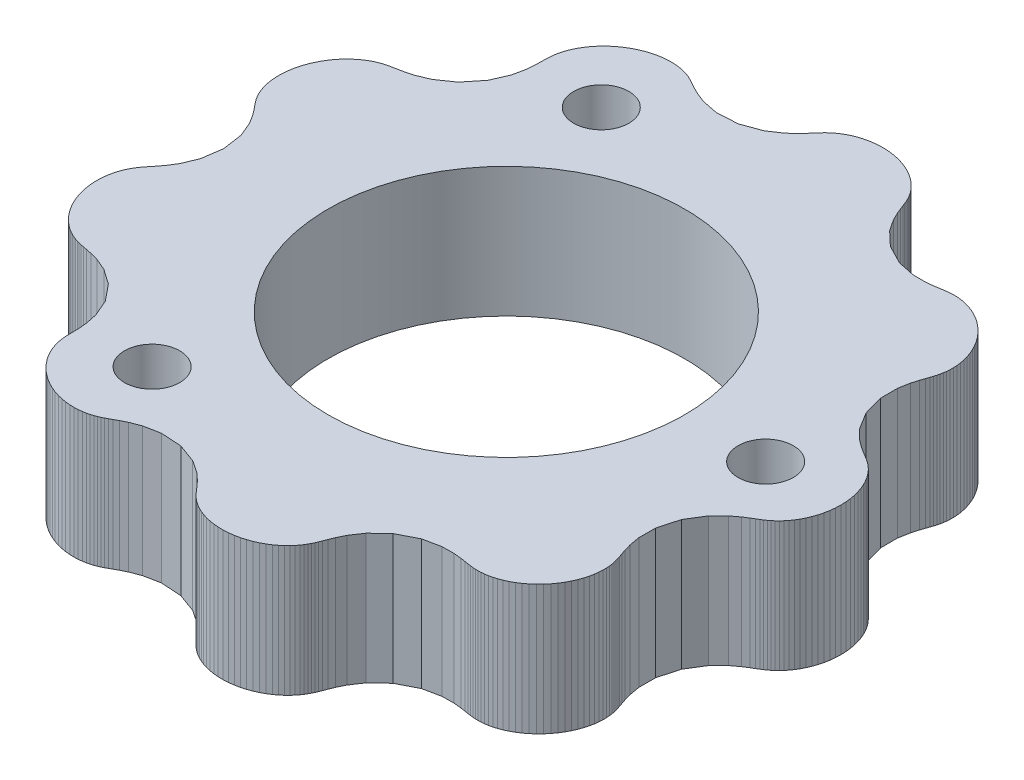
SolidWorks part; units mm, degrees
material "6061 Alloy"
ref_plane "Front" through (0, 0, 0) normal (0, 0, 1) x (1, 0, 0)
ref_plane "Top" through (0, 0, 0) normal (0, 1, 0) x (1, 0, 0)
ref_plane "Right" through (0, 0, 0) normal (1, 0, 0) x (0, 0, -1)
sketch "Sketch1" plane through (0, 0, 0) normal (0, 1, 0) x (1, 0, 0)
  line L0 (15.113, 0) -> (15.1037, 0.2524)
  line L1 (15.1037, 0.2524) -> (15.0761, 0.5014)
  line L2 (15.0761, 0.5014) -> (15.0311, 0.744)
  line L3 (15.0311, 0.744) -> (14.9699, 0.9771)
  line L4 (14.9699, 0.9771) -> (14.8944, 1.198)
  line L5 (14.8944, 1.198) -> (14.8069, 1.4044)
  line L6 (14.8069, 1.4044) -> (14.7097, 1.5946)
  line L7 (14.7097, 1.5946) -> (14.6056, 1.7674)
  line L8 (14.6056, 1.7674) -> (14.4973, 1.922)
  line L9 (14.4973, 1.922) -> (14.3874, 2.0586)
  line L10 (14.3874, 2.0586) -> (14.2779, 2.1778)
  line L11 (14.2779, 2.1778) -> (14.1706, 2.2811)
  line L12 (14.1706, 2.2811) -> (14.0658, 2.3708)
  line L13 (14.0658, 2.3708) -> (13.9626, 2.4499)
  line L14 (13.9626, 2.4499) -> (13.8577, 2.5227)
  line L15 (13.8577, 2.5227) -> (13.7444, 2.5952)
  line L16 (13.7444, 2.5952) -> (13.6106, 2.6762)
  line L17 (13.6106, 2.6762) -> (13.4356, 2.7811)
  line L18 (13.4356, 2.7811) -> (13.1874, 2.9387)
  line L19 (13.1874, 2.9387) -> (12.8245, 3.2087)
  line L20 (12.8245, 3.2087) -> (12.3314, 3.7011)
  line L21 (12.3314, 3.7011) -> (11.8258, 4.5171)
  line L22 (11.8258, 4.5171) -> (11.5537, 5.5075)
  line L23 (11.5537, 5.5075) -> (11.55, 6.3294)
  line L24 (11.55, 6.3294) -> (11.6479, 6.8716)
  line L25 (11.6479, 6.8716) -> (11.7462, 7.2119)
  line L26 (11.7462, 7.2119) -> (11.8222, 7.4368)
  line L27 (11.8222, 7.4368) -> (11.879, 7.6008)
  line L28 (11.879, 7.6008) -> (11.9232, 7.7357)
  line L29 (11.9232, 7.7357) -> (11.9594, 7.8598)
  line L30 (11.9594, 7.8598) -> (11.9899, 7.9842)
  line L31 (11.9899, 7.9842) -> (12.0151, 8.1157)
  line L32 (12.0151, 8.1157) -> (12.0342, 8.2582)
  line L33 (12.0342, 8.2582) -> (12.0455, 8.4138)
  line L34 (12.0455, 8.4138) -> (12.047, 8.5831)
  line L35 (12.047, 8.5831) -> (12.0365, 8.7657)
  line L36 (12.0365, 8.7657) -> (12.012, 8.9602)
  line L37 (12.012, 8.9602) -> (11.9717, 9.1647)
  line L38 (11.9717, 9.1647) -> (11.9141, 9.3767)
  line L39 (11.9141, 9.3767) -> (11.8383, 9.5933)
  line L40 (11.8383, 9.5933) -> (11.7436, 9.8115)
  line L41 (11.7436, 9.8115) -> (11.6304, 10.0281)
  line L42 (11.6304, 10.0281) -> (11.4991, 10.2398)
  line L43 (11.4991, 10.2398) -> (11.3509, 10.4435)
  line L44 (11.3509, 10.4435) -> (11.1876, 10.6365)
  line L45 (11.1876, 10.6365) -> (11.0114, 10.8162)
  line L46 (11.0114, 10.8162) -> (10.8247, 10.9805)
  line L47 (10.8247, 10.9805) -> (10.6304, 11.1277)
  line L48 (10.6304, 11.1277) -> (10.4316, 11.2567)
  line L49 (10.4316, 11.2567) -> (10.2314, 11.3669)
  line L50 (10.2314, 11.3669) -> (10.033, 11.4584)
  line L51 (10.033, 11.4584) -> (9.8393, 11.5316)
  line L52 (9.8393, 11.5316) -> (9.6529, 11.5876)
  line L53 (9.6529, 11.5876) -> (9.4761, 11.628)
  line L54 (9.4761, 11.628) -> (9.3104, 11.6545)
  line L55 (9.3104, 11.6545) -> (9.1565, 11.6691)
  line L56 (9.1565, 11.6691) -> (9.0141, 11.6741)
  line L57 (9.0141, 11.6741) -> (8.8811, 11.6714)
  line L58 (8.8811, 11.6714) -> (8.7536, 11.6623)
  line L59 (8.7536, 11.6623) -> (8.6244, 11.6475)
  line L60 (8.6244, 11.6475) -> (8.4816, 11.6267)
  line L61 (8.4816, 11.6267) -> (8.305, 11.5984)
  line L62 (8.305, 11.5984) -> (8.0605, 11.5618)
  line L63 (8.0605, 11.5618) -> (7.6906, 11.5252)
  line L64 (7.6906, 11.5252) -> (7.1123, 11.532)
  line L65 (7.1123, 11.532) -> (6.2778, 11.7054)
  line L66 (6.2778, 11.7054) -> (5.3573, 12.1787)
  line L67 (5.3573, 12.1787) -> (4.6782, 12.8227)
  line L68 (4.6782, 12.8227) -> (4.3077, 13.3763)
  line L69 (4.3077, 13.3763) -> (4.1189, 13.7632)
  line L70 (4.1189, 13.7632) -> (4.013, 14.0236)
  line L71 (4.013, 14.0236) -> (3.9428, 14.2077)
  line L72 (3.9428, 14.2077) -> (3.8871, 14.3502)
  line L73 (3.8871, 14.3502) -> (3.8355, 14.4729)
  line L74 (3.8355, 14.4729) -> (3.7815, 14.5885)
  line L75 (3.7815, 14.5885) -> (3.7206, 14.7041)
  line L76 (3.7206, 14.7041) -> (3.6492, 14.8234)
  line L77 (3.6492, 14.8234) -> (3.5645, 14.9476)
  line L78 (3.5645, 14.9476) -> (3.4642, 15.0766)
  line L79 (3.4642, 15.0766) -> (3.3469, 15.2088)
  line L80 (3.3469, 15.2088) -> (3.2113, 15.3424)
  line L81 (3.2113, 15.3424) -> (3.0572, 15.4746)
  line L82 (3.0572, 15.4746) -> (2.8848, 15.6027)
  line L83 (2.8848, 15.6027) -> (2.6948, 15.7239)
  line L84 (2.6948, 15.7239) -> (2.4886, 15.8353)
  line L85 (2.4886, 15.8353) -> (2.2682, 15.9346)
  line L86 (2.2682, 15.9346) -> (2.036, 16.0194)
  line L87 (2.036, 16.0194) -> (1.7946, 16.0879)
  line L88 (1.7946, 16.0879) -> (1.5472, 16.1389)
  line L89 (1.5472, 16.1389) -> (1.2969, 16.1715)
  line L90 (1.2969, 16.1715) -> (1.047, 16.1855)
  line L91 (1.047, 16.1855) -> (0.8009, 16.1813)
  line L92 (0.8009, 16.1813) -> (0.5617, 16.1596)
  line L93 (0.5617, 16.1596) -> (0.3322, 16.1219)
  line L94 (0.3322, 16.1219) -> (0.1152, 16.0701)
  line L95 (0.1152, 16.0701) -> (-0.0873, 16.0062)
  line L96 (-0.0873, 16.0062) -> (-0.2736, 15.9328)
  line L97 (-0.2736, 15.9328) -> (-0.4428, 15.8523)
  line L98 (-0.4428, 15.8523) -> (-0.5944, 15.7674)
  line L99 (-0.5944, 15.7674) -> (-0.729, 15.6802)
  line L100 (-0.729, 15.6802) -> (-0.8477, 15.5923)
  line L101 (-0.8477, 15.5923) -> (-0.9528, 15.5047)
  line L102 (-0.9528, 15.5047) -> (-1.0477, 15.4167)
  line L103 (-1.0477, 15.4167) -> (-1.1374, 15.3255)
  line L104 (-1.1374, 15.3255) -> (-1.2291, 15.2251)
  line L105 (-1.2291, 15.2251) -> (-1.3345, 15.1043)
  line L106 (-1.3345, 15.1043) -> (-1.4732, 14.9447)
  line L107 (-1.4732, 14.9447) -> (-1.682, 14.7187)
  line L108 (-1.682, 14.7187) -> (-2.0315, 14.3967)
  line L109 (-2.0315, 14.3967) -> (-2.6365, 13.9915)
  line L110 (-2.6365, 13.9915) -> (-3.5585, 13.6551)
  line L111 (-3.5585, 13.6551) -> (-4.5719, 13.5925)
  line L112 (-4.5719, 13.5925) -> (-5.3478, 13.7456)
  line L113 (-5.3478, 13.7456) -> (-5.8372, 13.9345)
  line L114 (-5.8372, 13.9345) -> (-6.1394, 14.0854)
  line L115 (-6.1394, 14.0854) -> (-6.3393, 14.1953)
  line L116 (-6.3393, 14.1953) -> (-6.4869, 14.2772)
  line L117 (-6.4869, 14.2772) -> (-6.6103, 14.3428)
  line L118 (-6.6103, 14.3428) -> (-6.726, 14.3992)
  line L119 (-6.726, 14.3992) -> (-6.8438, 14.4504)
  line L120 (-6.8438, 14.4504) -> (-6.9701, 14.4976)
  line L121 (-6.9701, 14.4976) -> (-7.1086, 14.5406)
  line L122 (-7.1086, 14.5406) -> (-7.2615, 14.5781)
  line L123 (-7.2615, 14.5781) -> (-7.4297, 14.608)
  line L124 (-7.4297, 14.608) -> (-7.6129, 14.6282)
  line L125 (-7.6129, 14.6282) -> (-7.8102, 14.6364)
  line L126 (-7.8102, 14.6364) -> (-8.0199, 14.6306)
  line L127 (-8.0199, 14.6306) -> (-8.2397, 14.6088)
  line L128 (-8.2397, 14.6088) -> (-8.4669, 14.5697)
  line L129 (-8.4669, 14.5697) -> (-8.6986, 14.5124)
  line L130 (-8.6986, 14.5124) -> (-8.9315, 14.4364)
  line L131 (-8.9315, 14.4364) -> (-9.1623, 14.3418)
  line L132 (-9.1623, 14.3418) -> (-9.388, 14.2293)
  line L133 (-9.388, 14.2293) -> (-9.6053, 14.1003)
  line L134 (-9.6053, 14.1003) -> (-9.8115, 13.9564)
  line L135 (-9.8115, 13.9564) -> (-10.0041, 13.7997)
  line L136 (-10.0041, 13.7997) -> (-10.1809, 13.633)
  line L137 (-10.1809, 13.633) -> (-10.3405, 13.4589)
  line L138 (-10.3405, 13.4589) -> (-10.4818, 13.2806)
  line L139 (-10.4818, 13.2806) -> (-10.6042, 13.1011)
  line L140 (-10.6042, 13.1011) -> (-10.7079, 12.9234)
  line L141 (-10.7079, 12.9234) -> (-10.7935, 12.7502)
  line L142 (-10.7935, 12.7502) -> (-10.8621, 12.5839)
  line L143 (-10.8621, 12.5839) -> (-10.9154, 12.4264)
  line L144 (-10.9154, 12.4264) -> (-10.9551, 12.2785)
  line L145 (-10.9551, 12.2785) -> (-10.9837, 12.1401)
  line L146 (-10.9837, 12.1401) -> (-11.0031, 12.0093)
  line L147 (-11.0031, 12.0093) -> (-11.0156, 11.8823)
  line L148 (-11.0156, 11.8823) -> (-11.0231, 11.7516)
  line L149 (-11.0231, 11.7516) -> (-11.0271, 11.6047)
  line L150 (-11.0271, 11.6047) -> (-11.0299, 11.4203)
  line L151 (-11.0299, 11.4203) -> (-11.0374, 11.1626)
  line L152 (-11.0374, 11.1626) -> (-11.0704, 10.7738)
  line L153 (-11.0704, 10.7738) -> (-11.193, 10.1795)
  line L154 (-11.193, 10.1795) -> (-11.5414, 9.3696)
  line L155 (-11.5414, 9.3696) -> (-12.1963, 8.5629)
  line L156 (-12.1963, 8.5629) -> (-12.9426, 8.0428)
  line L157 (-12.9426, 8.0428) -> (-13.5295, 7.7974)
  line L158 (-13.5295, 7.7974) -> (-13.9245, 7.6885)
  line L159 (-13.9245, 7.6885) -> (-14.1879, 7.6331)
  line L160 (-14.1879, 7.6331) -> (-14.3749, 7.5972)
  line L161 (-14.3749, 7.5972) -> (-14.5218, 7.5675)
  line L162 (-14.5218, 7.5675) -> (-14.6503, 7.5377)
  line L163 (-14.6503, 7.5377) -> (-14.7733, 7.504)
  line L164 (-14.7733, 7.504) -> (-14.8982, 7.4631)
  line L165 (-14.8982, 7.4631) -> (-15.0288, 7.4122)
  line L166 (-15.0288, 7.4122) -> (-15.1667, 7.3489)
  line L167 (-15.1667, 7.3489) -> (-15.3119, 7.2709)
  line L168 (-15.3119, 7.2709) -> (-15.4631, 7.1764)
  line L169 (-15.4631, 7.1764) -> (-15.6185, 7.064)
  line L170 (-15.6185, 7.064) -> (-15.7755, 6.9331)
  line L171 (-15.7755, 6.9331) -> (-15.9313, 6.7835)
  line L172 (-15.9313, 6.7835) -> (-16.0831, 6.6154)
  line L173 (-16.0831, 6.6154) -> (-16.2277, 6.4298)
  line L174 (-16.2277, 6.4298) -> (-16.3625, 6.2284)
  line L175 (-16.3625, 6.2284) -> (-16.4848, 6.0129)
  line L176 (-16.4848, 6.0129) -> (-16.5925, 5.786)
  line L177 (-16.5925, 5.786) -> (-16.6838, 5.5503)
  line L178 (-16.6838, 5.5503) -> (-16.7573, 5.309)
  line L179 (-16.7573, 5.309) -> (-16.8125, 5.0653)
  line L180 (-16.8125, 5.0653) -> (-16.849, 4.8224)
  line L181 (-16.849, 4.8224) -> (-16.8672, 4.5837)
  line L182 (-16.8672, 4.5837) -> (-16.8681, 4.3522)
  line L183 (-16.8681, 4.3522) -> (-16.853, 4.1307)
  line L184 (-16.853, 4.1307) -> (-16.8238, 3.9216)
  line L185 (-16.8238, 3.9216) -> (-16.7826, 3.7271)
  line L186 (-16.7826, 3.7271) -> (-16.7318, 3.5483)
  line L187 (-16.7318, 3.5483) -> (-16.6738, 3.3861)
  line L188 (-16.6738, 3.3861) -> (-16.6108, 3.2402)
  line L189 (-16.6108, 3.2402) -> (-16.5447, 3.1096)
  line L190 (-16.5447, 3.1096) -> (-16.4764, 2.9922)
  line L191 (-16.4764, 2.9922) -> (-16.4059, 2.8843)
  line L192 (-16.4059, 2.8843) -> (-16.331, 2.7802)
  line L193 (-16.331, 2.7802) -> (-16.2466, 2.6713)
  line L194 (-16.2466, 2.6713) -> (-16.1432, 2.5436)
  line L195 (-16.1432, 2.5436) -> (-16.0053, 2.3728)
  line L196 (-16.0053, 2.3728) -> (-15.8117, 2.1151)
  line L197 (-15.8117, 2.1151) -> (-15.5478, 1.6912)
  line L198 (-15.5478, 1.6912) -> (-15.2569, 0.9896)
  line L199 (-15.2569, 0.9896) -> (-15.113, 0)
  line L200 (-15.113, 0) -> (-15.2569, -0.9896)
  line L201 (-15.2569, -0.9896) -> (-15.5478, -1.6912)
  line L202 (-15.5478, -1.6912) -> (-15.8117, -2.1151)
  line L203 (-15.8117, -2.1151) -> (-16.0053, -2.3728)
  line L204 (-16.0053, -2.3728) -> (-16.1432, -2.5436)
  line L205 (-16.1432, -2.5436) -> (-16.2466, -2.6713)
  line L206 (-16.2466, -2.6713) -> (-16.331, -2.7802)
  line L207 (-16.331, -2.7802) -> (-16.4059, -2.8843)
  line L208 (-16.4059, -2.8843) -> (-16.4764, -2.9922)
  line L209 (-16.4764, -2.9922) -> (-16.5447, -3.1096)
  line L210 (-16.5447, -3.1096) -> (-16.6108, -3.2402)
  line L211 (-16.6108, -3.2402) -> (-16.6738, -3.3861)
  line L212 (-16.6738, -3.3861) -> (-16.7318, -3.5483)
  line L213 (-16.7318, -3.5483) -> (-16.7826, -3.7271)
  line L214 (-16.7826, -3.7271) -> (-16.8238, -3.9216)
  line L215 (-16.8238, -3.9216) -> (-16.853, -4.1307)
  line L216 (-16.853, -4.1307) -> (-16.8681, -4.3522)
  line L217 (-16.8681, -4.3522) -> (-16.8672, -4.5837)
  line L218 (-16.8672, -4.5837) -> (-16.849, -4.8224)
  line L219 (-16.849, -4.8224) -> (-16.8125, -5.0653)
  line L220 (-16.8125, -5.0653) -> (-16.7573, -5.309)
  line L221 (-16.7573, -5.309) -> (-16.6838, -5.5503)
  line L222 (-16.6838, -5.5503) -> (-16.5925, -5.786)
  line L223 (-16.5925, -5.786) -> (-16.4848, -6.0129)
  line L224 (-16.4848, -6.0129) -> (-16.3625, -6.2284)
  line L225 (-16.3625, -6.2284) -> (-16.2277, -6.4298)
  line L226 (-16.2277, -6.4298) -> (-16.0831, -6.6154)
  line L227 (-16.0831, -6.6154) -> (-15.9313, -6.7835)
  line L228 (-15.9313, -6.7835) -> (-15.7755, -6.9331)
  line L229 (-15.7755, -6.9331) -> (-15.6185, -7.064)
  line L230 (-15.6185, -7.064) -> (-15.4631, -7.1764)
  line L231 (-15.4631, -7.1764) -> (-15.3119, -7.2709)
  line L232 (-15.3119, -7.2709) -> (-15.1667, -7.3489)
  line L233 (-15.1667, -7.3489) -> (-15.0288, -7.4122)
  line L234 (-15.0288, -7.4122) -> (-14.8982, -7.4631)
  line L235 (-14.8982, -7.4631) -> (-14.7733, -7.504)
  line L236 (-14.7733, -7.504) -> (-14.6503, -7.5377)
  line L237 (-14.6503, -7.5377) -> (-14.5218, -7.5675)
  line L238 (-14.5218, -7.5675) -> (-14.3749, -7.5972)
  line L239 (-14.3749, -7.5972) -> (-14.1879, -7.6331)
  line L240 (-14.1879, -7.6331) -> (-13.9245, -7.6885)
  line L241 (-13.9245, -7.6885) -> (-13.5295, -7.7974)
  line L242 (-13.5295, -7.7974) -> (-12.9426, -8.0428)
  line L243 (-12.9426, -8.0428) -> (-12.1963, -8.5629)
  line L244 (-12.1963, -8.5629) -> (-11.5414, -9.3696)
  line L245 (-11.5414, -9.3696) -> (-11.193, -10.1795)
  line L246 (-11.193, -10.1795) -> (-11.0704, -10.7738)
  line L247 (-11.0704, -10.7738) -> (-11.0374, -11.1626)
  line L248 (-11.0374, -11.1626) -> (-11.0299, -11.4203)
  line L249 (-11.0299, -11.4203) -> (-11.0271, -11.6047)
  line L250 (-11.0271, -11.6047) -> (-11.0231, -11.7516)
  line L251 (-11.0231, -11.7516) -> (-11.0156, -11.8823)
  line L252 (-11.0156, -11.8823) -> (-11.0031, -12.0093)
  line L253 (-11.0031, -12.0093) -> (-10.9837, -12.1401)
  line L254 (-10.9837, -12.1401) -> (-10.9551, -12.2785)
  line L255 (-10.9551, -12.2785) -> (-10.9154, -12.4264)
  line L256 (-10.9154, -12.4264) -> (-10.8621, -12.5839)
  line L257 (-10.8621, -12.5839) -> (-10.7935, -12.7502)
  line L258 (-10.7935, -12.7502) -> (-10.7079, -12.9234)
  line L259 (-10.7079, -12.9234) -> (-10.6042, -13.1011)
  line L260 (-10.6042, -13.1011) -> (-10.4818, -13.2806)
  line L261 (-10.4818, -13.2806) -> (-10.3405, -13.4589)
  line L262 (-10.3405, -13.4589) -> (-10.1809, -13.633)
  line L263 (-10.1809, -13.633) -> (-10.0041, -13.7997)
  line L264 (-10.0041, -13.7997) -> (-9.8115, -13.9564)
  line L265 (-9.8115, -13.9564) -> (-9.6053, -14.1003)
  line L266 (-9.6053, -14.1003) -> (-9.388, -14.2293)
  line L267 (-9.388, -14.2293) -> (-9.1623, -14.3418)
  line L268 (-9.1623, -14.3418) -> (-8.9315, -14.4364)
  line L269 (-8.9315, -14.4364) -> (-8.6986, -14.5124)
  line L270 (-8.6986, -14.5124) -> (-8.4669, -14.5697)
  line L271 (-8.4669, -14.5697) -> (-8.2397, -14.6088)
  line L272 (-8.2397, -14.6088) -> (-8.0199, -14.6306)
  line L273 (-8.0199, -14.6306) -> (-7.8102, -14.6364)
  line L274 (-7.8102, -14.6364) -> (-7.6129, -14.6282)
  line L275 (-7.6129, -14.6282) -> (-7.4297, -14.608)
  line L276 (-7.4297, -14.608) -> (-7.2615, -14.5781)
  line L277 (-7.2615, -14.5781) -> (-7.1086, -14.5406)
  line L278 (-7.1086, -14.5406) -> (-6.9701, -14.4976)
  line L279 (-6.9701, -14.4976) -> (-6.8438, -14.4504)
  line L280 (-6.8438, -14.4504) -> (-6.726, -14.3992)
  line L281 (-6.726, -14.3992) -> (-6.6103, -14.3428)
  line L282 (-6.6103, -14.3428) -> (-6.4869, -14.2772)
  line L283 (-6.4869, -14.2772) -> (-6.3393, -14.1953)
  line L284 (-6.3393, -14.1953) -> (-6.1394, -14.0854)
  line L285 (-6.1394, -14.0854) -> (-5.8372, -13.9345)
  line L286 (-5.8372, -13.9345) -> (-5.3478, -13.7456)
  line L287 (-5.3478, -13.7456) -> (-4.5719, -13.5925)
  line L288 (-4.5719, -13.5925) -> (-3.5585, -13.6551)
  line L289 (-3.5585, -13.6551) -> (-2.6365, -13.9915)
  line L290 (-2.6365, -13.9915) -> (-2.0315, -14.3967)
  line L291 (-2.0315, -14.3967) -> (-1.682, -14.7187)
  line L292 (-1.682, -14.7187) -> (-1.4732, -14.9447)
  line L293 (-1.4732, -14.9447) -> (-1.3345, -15.1043)
  line L294 (-1.3345, -15.1043) -> (-1.2291, -15.2251)
  line L295 (-1.2291, -15.2251) -> (-1.1374, -15.3255)
  line L296 (-1.1374, -15.3255) -> (-1.0477, -15.4167)
  line L297 (-1.0477, -15.4167) -> (-0.9528, -15.5047)
  line L298 (-0.9528, -15.5047) -> (-0.8477, -15.5923)
  line L299 (-0.8477, -15.5923) -> (-0.729, -15.6802)
  line L300 (-0.729, -15.6802) -> (-0.5944, -15.7674)
  line L301 (-0.5944, -15.7674) -> (-0.4428, -15.8523)
  line L302 (-0.4428, -15.8523) -> (-0.2736, -15.9328)
  line L303 (-0.2736, -15.9328) -> (-0.0873, -16.0062)
  line L304 (-0.0873, -16.0062) -> (0.1152, -16.0701)
  line L305 (0.1152, -16.0701) -> (0.3322, -16.1219)
  line L306 (0.3322, -16.1219) -> (0.5617, -16.1596)
  line L307 (0.5617, -16.1596) -> (0.8009, -16.1813)
  line L308 (0.8009, -16.1813) -> (1.047, -16.1855)
  line L309 (1.047, -16.1855) -> (1.2969, -16.1715)
  line L310 (1.2969, -16.1715) -> (1.5472, -16.1389)
  line L311 (1.5472, -16.1389) -> (1.7946, -16.0879)
  line L312 (1.7946, -16.0879) -> (2.036, -16.0194)
  line L313 (2.036, -16.0194) -> (2.2682, -15.9346)
  line L314 (2.2682, -15.9346) -> (2.4886, -15.8353)
  line L315 (2.4886, -15.8353) -> (2.6948, -15.7239)
  line L316 (2.6948, -15.7239) -> (2.8848, -15.6027)
  line L317 (2.8848, -15.6027) -> (3.0572, -15.4746)
  line L318 (3.0572, -15.4746) -> (3.2113, -15.3424)
  line L319 (3.2113, -15.3424) -> (3.3469, -15.2088)
  line L320 (3.3469, -15.2088) -> (3.4642, -15.0766)
  line L321 (3.4642, -15.0766) -> (3.5645, -14.9476)
  line L322 (3.5645, -14.9476) -> (3.6492, -14.8234)
  line L323 (3.6492, -14.8234) -> (3.7206, -14.7041)
  line L324 (3.7206, -14.7041) -> (3.7815, -14.5885)
  line L325 (3.7815, -14.5885) -> (3.8355, -14.4729)
  line L326 (3.8355, -14.4729) -> (3.8871, -14.3502)
  line L327 (3.8871, -14.3502) -> (3.9428, -14.2077)
  line L328 (3.9428, -14.2077) -> (4.013, -14.0236)
  line L329 (4.013, -14.0236) -> (4.1189, -13.7632)
  line L330 (4.1189, -13.7632) -> (4.3077, -13.3763)
  line L331 (4.3077, -13.3763) -> (4.6782, -12.8227)
  line L332 (4.6782, -12.8227) -> (5.3573, -12.1787)
  line L333 (5.3573, -12.1787) -> (6.2778, -11.7054)
  line L334 (6.2778, -11.7054) -> (7.1123, -11.532)
  line L335 (7.1123, -11.532) -> (7.6906, -11.5252)
  line L336 (7.6906, -11.5252) -> (8.0605, -11.5618)
  line L337 (8.0605, -11.5618) -> (8.305, -11.5984)
  line L338 (8.305, -11.5984) -> (8.4816, -11.6267)
  line L339 (8.4816, -11.6267) -> (8.6244, -11.6475)
  line L340 (8.6244, -11.6475) -> (8.7536, -11.6623)
  line L341 (8.7536, -11.6623) -> (8.8811, -11.6714)
  line L342 (8.8811, -11.6714) -> (9.0141, -11.6741)
  line L343 (9.0141, -11.6741) -> (9.1565, -11.6691)
  line L344 (9.1565, -11.6691) -> (9.3104, -11.6545)
  line L345 (9.3104, -11.6545) -> (9.4761, -11.628)
  line L346 (9.4761, -11.628) -> (9.6529, -11.5876)
  line L347 (9.6529, -11.5876) -> (9.8393, -11.5316)
  line L348 (9.8393, -11.5316) -> (10.033, -11.4584)
  line L349 (10.033, -11.4584) -> (10.2314, -11.3669)
  line L350 (10.2314, -11.3669) -> (10.4316, -11.2567)
  line L351 (10.4316, -11.2567) -> (10.6304, -11.1277)
  line L352 (10.6304, -11.1277) -> (10.8247, -10.9805)
  line L353 (10.8247, -10.9805) -> (11.0114, -10.8162)
  line L354 (11.0114, -10.8162) -> (11.1876, -10.6365)
  line L355 (11.1876, -10.6365) -> (11.3509, -10.4435)
  line L356 (11.3509, -10.4435) -> (11.4991, -10.2398)
  line L357 (11.4991, -10.2398) -> (11.6304, -10.0281)
  line L358 (11.6304, -10.0281) -> (11.7436, -9.8115)
  line L359 (11.7436, -9.8115) -> (11.8383, -9.5933)
  line L360 (11.8383, -9.5933) -> (11.9141, -9.3767)
  line L361 (11.9141, -9.3767) -> (11.9717, -9.1647)
  line L362 (11.9717, -9.1647) -> (12.012, -8.9602)
  line L363 (12.012, -8.9602) -> (12.0365, -8.7657)
  line L364 (12.0365, -8.7657) -> (12.047, -8.5831)
  line L365 (12.047, -8.5831) -> (12.0455, -8.4138)
  line L366 (12.0455, -8.4138) -> (12.0342, -8.2582)
  line L367 (12.0342, -8.2582) -> (12.0151, -8.1157)
  line L368 (12.0151, -8.1157) -> (11.9899, -7.9842)
  line L369 (11.9899, -7.9842) -> (11.9594, -7.8598)
  line L370 (11.9594, -7.8598) -> (11.9232, -7.7357)
  line L371 (11.9232, -7.7357) -> (11.879, -7.6008)
  line L372 (11.879, -7.6008) -> (11.8222, -7.4368)
  line L373 (11.8222, -7.4368) -> (11.7462, -7.2119)
  line L374 (11.7462, -7.2119) -> (11.6479, -6.8716)
  line L375 (11.6479, -6.8716) -> (11.55, -6.3294)
  line L376 (11.55, -6.3294) -> (11.5537, -5.5075)
  line L377 (11.5537, -5.5075) -> (11.8258, -4.5171)
  line L378 (11.8258, -4.5171) -> (12.3314, -3.7011)
  line L379 (12.3314, -3.7011) -> (12.8245, -3.2087)
  line L380 (12.8245, -3.2087) -> (13.1874, -2.9387)
  line L381 (13.1874, -2.9387) -> (13.4356, -2.7811)
  line L382 (13.4356, -2.7811) -> (13.6106, -2.6762)
  line L383 (13.6106, -2.6762) -> (13.7444, -2.5952)
  line L384 (13.7444, -2.5952) -> (13.8577, -2.5227)
  line L385 (13.8577, -2.5227) -> (13.9626, -2.4499)
  line L386 (13.9626, -2.4499) -> (14.0658, -2.3708)
  line L387 (14.0658, -2.3708) -> (14.1706, -2.2811)
  line L388 (14.1706, -2.2811) -> (14.2779, -2.1778)
  line L389 (14.2779, -2.1778) -> (14.3874, -2.0586)
  line L390 (14.3874, -2.0586) -> (14.4973, -1.922)
  line L391 (14.4973, -1.922) -> (14.6056, -1.7674)
  line L392 (14.6056, -1.7674) -> (14.7097, -1.5946)
  line L393 (14.7097, -1.5946) -> (14.8069, -1.4044)
  line L394 (14.8069, -1.4044) -> (14.8944, -1.198)
  line L395 (14.8944, -1.198) -> (14.9699, -0.9771)
  line L396 (14.9699, -0.9771) -> (15.0311, -0.744)
  line L397 (15.0311, -0.744) -> (15.0761, -0.5014)
  line L398 (15.0761, -0.5014) -> (15.1037, -0.2524)
  line L399 (15.1037, -0.2524) -> (15.113, 0)
  line L400 (13.1586, 2.8968) -> (12.7913, 3.1701) construction
  line L401 (12.7913, 3.1701) -> (12.2913, 3.6693) construction
  line L402 (12.2913, 3.6693) -> (11.7787, 4.4966) construction
  line L403 (11.7787, 4.4966) -> (11.5029, 5.5006) construction
  line L404 (11.5029, 5.5006) -> (11.4991, 6.3338) construction
  line L405 (11.4991, 6.3338) -> (11.5984, 6.8832) construction
  line L406 (11.5984, 6.8832) -> (11.6978, 7.2271) construction
  line L407 (11.6978, 7.2271) -> (11.7742, 7.4532) construction
  line L408 (11.7742, 7.4532) -> (11.8309, 7.6171) construction
  line L409 (11.8309, 7.6171) -> (11.8747, 7.7507) construction
  line L410 (11.8747, 7.7507) -> (11.9103, 7.873) construction
  line L411 (11.9103, 7.873) -> (11.9402, 7.9951) construction
  line L412 (11.9402, 7.9951) -> (11.9649, 8.1239) construction
  line L413 (11.9649, 8.1239) -> (11.9836, 8.2635) construction
  line L414 (11.9836, 8.2635) -> (11.9947, 8.4159) construction
  line L415 (11.9947, 8.4159) -> (11.9962, 8.5819) construction
  line L416 (11.9962, 8.5819) -> (11.9859, 8.7611) construction
  line L417 (11.9859, 8.7611) -> (11.9619, 8.9521) construction
  line L418 (11.9619, 8.9521) -> (11.9222, 9.1531) construction
  line L419 (11.9222, 9.1531) -> (11.8656, 9.3616) construction
  line L420 (11.8656, 9.3616) -> (11.7909, 9.5748) construction
  line L421 (11.7909, 9.5748) -> (11.6978, 9.7896) construction
  line L422 (11.6978, 9.7896) -> (11.5862, 10.0029) construction
  line L423 (11.5862, 10.0029) -> (11.4569, 10.2114) construction
  line L424 (11.4569, 10.2114) -> (11.3109, 10.4121) construction
  line L425 (11.3109, 10.4121) -> (11.1501, 10.6023) construction
  line L426 (11.1501, 10.6023) -> (10.9764, 10.7793) construction
  line L427 (10.9764, 10.7793) -> (10.7925, 10.9411) construction
  line L428 (10.7925, 10.9411) -> (10.6012, 11.086) construction
  line L429 (10.6012, 11.086) -> (10.4055, 11.213) construction
  line L430 (10.4055, 11.213) -> (10.2085, 11.3215) construction
  line L431 (10.2085, 11.3215) -> (10.0134, 11.4115) construction
  line L432 (10.0134, 11.4115) -> (9.8229, 11.4835) construction
  line L433 (9.8229, 11.4835) -> (9.6399, 11.5385) construction
  line L434 (9.6399, 11.5385) -> (9.4664, 11.5781) construction
  line L435 (9.4664, 11.5781) -> (9.304, 11.604) construction
  line L436 (9.304, 11.604) -> (9.1532, 11.6184) construction
  line L437 (9.1532, 11.6184) -> (9.0137, 11.6233) construction
  line L438 (9.0137, 11.6233) -> (8.8834, 11.6206) construction
  line L439 (8.8834, 11.6206) -> (8.7583, 11.6117) construction
  line L440 (8.7583, 11.6117) -> (8.631, 11.5972) construction
  line L441 (8.631, 11.5972) -> (8.4893, 11.5765) construction
  line L442 (8.4893, 11.5765) -> (8.3128, 11.5482) construction
  line L443 (8.3128, 11.5482) -> (8.0668, 11.5114) construction
  line L444 (8.0668, 11.5114) -> (7.6928, 11.4744) construction
  line L445 (7.6928, 11.4744) -> (7.1068, 11.4813) construction
  line L446 (7.1068, 11.4813) -> (6.2607, 11.6571) construction
  line L447 (6.2607, 11.6571) -> (5.3277, 12.1368) construction
  line L448 (5.3277, 12.1368) -> (4.6391, 12.7897) construction
  line L449 (4.6391, 12.7897) -> (4.2635, 13.3509) construction
  line L450 (4.2635, 13.3509) -> (4.0725, 13.7425) construction
  line L451 (4.0725, 13.7425) -> (3.9657, 14.005) construction
  line L452 (3.9657, 14.005) -> (3.8954, 14.1894) construction
  line L453 (3.8954, 14.1894) -> (3.8401, 14.3312) construction
  line L454 (3.8401, 14.3312) -> (3.7891, 14.4523) construction
  line L455 (3.7891, 14.4523) -> (3.736, 14.5659) construction
  line L456 (3.736, 14.5659) -> (3.6763, 14.6792) construction
  line L457 (3.6763, 14.6792) -> (3.6063, 14.796) construction
  line L458 (3.6063, 14.796) -> (3.5234, 14.9177) construction
  line L459 (3.5234, 14.9177) -> (3.4251, 15.0441) construction
  line L460 (3.4251, 15.0441) -> (3.31, 15.1738) construction
  line L461 (3.31, 15.1738) -> (3.1769, 15.3049) construction
  line L462 (3.1769, 15.3049) -> (3.0255, 15.4348) construction
  line L463 (3.0255, 15.4348) -> (2.8559, 15.5608) construction
  line L464 (2.8559, 15.5608) -> (2.669, 15.68) construction
  line L465 (2.669, 15.68) -> (2.4661, 15.7898) construction
  line L466 (2.4661, 15.7898) -> (2.2491, 15.8875) construction
  line L467 (2.2491, 15.8875) -> (2.0203, 15.971) construction
  line L468 (2.0203, 15.971) -> (1.7825, 16.0385) construction
  line L469 (1.7825, 16.0385) -> (1.5388, 16.0887) construction
  line L470 (1.5388, 16.0887) -> (1.2922, 16.1209) construction
  line L471 (1.2922, 16.1209) -> (1.046, 16.1347) construction
  line L472 (1.046, 16.1347) -> (0.8036, 16.1305) construction
  line L473 (0.8036, 16.1305) -> (0.5681, 16.1092) construction
  line L474 (0.5681, 16.1092) -> (0.3423, 16.0721) construction
  line L475 (0.3423, 16.0721) -> (0.1288, 16.0211) construction
  line L476 (0.1288, 16.0211) -> (-0.0703, 15.9583) construction
  line L477 (-0.0703, 15.9583) -> (-0.2534, 15.8862) construction
  line L478 (-0.2534, 15.8862) -> (-0.4194, 15.8072) construction
  line L479 (-0.4194, 15.8072) -> (-0.5682, 15.7239) construction
  line L480 (-0.5682, 15.7239) -> (-0.7, 15.6384) construction
  line L481 (-0.7, 15.6384) -> (-0.8163, 15.5524) construction
  line L482 (-0.8163, 15.5524) -> (-0.9193, 15.4666) construction
  line L483 (-0.9193, 15.4666) -> (-1.0123, 15.3803) construction
  line L484 (-1.0123, 15.3803) -> (-1.1005, 15.2906) construction
  line L485 (-1.1005, 15.2906) -> (-1.1912, 15.1912) construction
  line L486 (-1.1912, 15.1912) -> (-1.2962, 15.0709) construction
  line L487 (-1.2962, 15.0709) -> (-1.4354, 14.9108) construction
  line L488 (-1.4354, 14.9108) -> (-1.6461, 14.6827) construction
  line L489 (-1.6461, 14.6827) -> (-2, 14.3566) construction
  line L490 (-2, 14.3566) -> (-2.6133, 13.9459) construction
  line L491 (-2.6133, 13.9459) -> (-3.548, 13.6048) construction
  line L492 (-3.548, 13.6048) -> (-4.5753, 13.5414) construction
  line L493 (-4.5753, 13.5414) -> (-5.362, 13.6966) construction
  line L494 (-5.362, 13.6966) -> (-5.8577, 13.888) construction
  line L495 (-5.8577, 13.888) -> (-6.163, 14.0404) construction
  line L496 (-6.163, 14.0404) -> (-6.3639, 14.1508) construction
  line L497 (-6.3639, 14.1508) -> (-6.5111, 14.2326) construction
  line L498 (-6.5111, 14.2326) -> (-6.6334, 14.2975) construction
  line L499 (-6.6334, 14.2975) -> (-6.7472, 14.3531) construction
  line L500 (-6.7472, 14.3531) -> (-6.8628, 14.4033) construction
  line L501 (-6.8628, 14.4033) -> (-6.9865, 14.4495) construction
  line L502 (-6.9865, 14.4495) -> (-7.1222, 14.4916) construction
  line L503 (-7.1222, 14.4916) -> (-7.272, 14.5283) construction
  line L504 (-7.272, 14.5283) -> (-7.4369, 14.5577) construction
  line L505 (-7.4369, 14.5577) -> (-7.6168, 14.5775) construction
  line L506 (-7.6168, 14.5775) -> (-7.8106, 14.5856) construction
  line L507 (-7.8106, 14.5856) -> (-8.0167, 14.5799) construction
  line L508 (-8.0167, 14.5799) -> (-8.2329, 14.5585) construction
  line L509 (-8.2329, 14.5585) -> (-8.4565, 14.52) construction
  line L510 (-8.4565, 14.52) -> (-8.6845, 14.4635) construction
  line L511 (-8.6845, 14.4635) -> (-8.9139, 14.3887) construction
  line L512 (-8.9139, 14.3887) -> (-9.1414, 14.2955) construction
  line L513 (-9.1414, 14.2955) -> (-9.3637, 14.1847) construction
  line L514 (-9.3637, 14.1847) -> (-9.5778, 14.0576) construction
  line L515 (-9.5778, 14.0576) -> (-9.7809, 13.9158) construction
  line L516 (-9.7809, 13.9158) -> (-9.9706, 13.7615) construction
  line L517 (-9.9706, 13.7615) -> (-10.1447, 13.5973) construction
  line L518 (-10.1447, 13.5973) -> (-10.3018, 13.4259) construction
  line L519 (-10.3018, 13.4259) -> (-10.4408, 13.2505) construction
  line L520 (-10.4408, 13.2505) -> (-10.5612, 13.0739) construction
  line L521 (-10.5612, 13.0739) -> (-10.6632, 12.8993) construction
  line L522 (-10.6632, 12.8993) -> (-10.7472, 12.7292) construction
  line L523 (-10.7472, 12.7292) -> (-10.8145, 12.5661) construction
  line L524 (-10.8145, 12.5661) -> (-10.8667, 12.4116) construction
  line L525 (-10.8667, 12.4116) -> (-10.9057, 12.2668) construction
  line L526 (-10.9057, 12.2668) -> (-10.9336, 12.1312) construction
  line L527 (-10.9336, 12.1312) -> (-10.9527, 12.0031) construction
  line L528 (-10.9527, 12.0031) -> (-10.965, 11.8784) construction
  line L529 (-10.965, 11.8784) -> (-10.9723, 11.7495) construction
  line L530 (-10.9723, 11.7495) -> (-10.9763, 11.6036) construction
  line L531 (-10.9763, 11.6036) -> (-10.9791, 11.4192) construction
  line L532 (-10.9791, 11.4192) -> (-10.9867, 11.1597) construction
  line L533 (-10.9867, 11.1597) -> (-11.0201, 10.7665) construction
  line L534 (-11.0201, 10.7665) -> (-11.1443, 10.1642) construction
  line L535 (-11.1443, 10.1642) -> (-11.4976, 9.3431) construction
  line L536 (-11.4976, 9.3431) -> (-12.1614, 8.5253) construction
  line L537 (-12.1614, 8.5253) -> (-12.918, 7.998) construction
  line L538 (-12.918, 7.998) -> (-13.5129, 7.7493) construction
  line L539 (-13.5129, 7.7493) -> (-13.9125, 7.6391) construction
  line L540 (-13.9125, 7.6391) -> (-14.1778, 7.5833) construction
  line L541 (-14.1778, 7.5833) -> (-14.3651, 7.5473) construction
  line L542 (-14.3651, 7.5473) -> (-14.5111, 7.5178) construction
  line L543 (-14.5111, 7.5178) -> (-14.6379, 7.4885) construction
  line L544 (-14.6379, 7.4885) -> (-14.7587, 7.4553) construction
  line L545 (-14.7587, 7.4553) -> (-14.8811, 7.4152) construction
  line L546 (-14.8811, 7.4152) -> (-15.009, 7.3654) construction
  line L547 (-15.009, 7.3654) -> (-15.1441, 7.3034) construction
  line L548 (-15.1441, 7.3034) -> (-15.2864, 7.2269) construction
  line L549 (-15.2864, 7.2269) -> (-15.4347, 7.1342) construction
  line L550 (-15.4347, 7.1342) -> (-15.5873, 7.0239) construction
  line L551 (-15.5873, 7.0239) -> (-15.7416, 6.8953) construction
  line L552 (-15.7416, 6.8953) -> (-15.8948, 6.7481) construction
  line L553 (-15.8948, 6.7481) -> (-16.0441, 6.5827) construction
  line L554 (-16.0441, 6.5827) -> (-16.1865, 6.4001) construction
  line L555 (-16.1865, 6.4001) -> (-16.3192, 6.2017) construction
  line L556 (-16.3192, 6.2017) -> (-16.4397, 5.9895) construction
  line L557 (-16.4397, 5.9895) -> (-16.5458, 5.7659) construction
  line L558 (-16.5458, 5.7659) -> (-16.6357, 5.5337) construction
  line L559 (-16.6357, 5.5337) -> (-16.7082, 5.296) construction
  line L560 (-16.7082, 5.296) -> (-16.7625, 5.0559) construction
  line L561 (-16.7625, 5.0559) -> (-16.7985, 4.8167) construction
  line L562 (-16.7985, 4.8167) -> (-16.8164, 4.5817) construction
  line L563 (-16.8164, 4.5817) -> (-16.8173, 4.3538) construction
  line L564 (-16.8173, 4.3538) -> (-16.8024, 4.1359) construction
  line L565 (-16.8024, 4.1359) -> (-16.7737, 3.9304) construction
  line L566 (-16.7737, 3.9304) -> (-16.7333, 3.7393) construction
  line L567 (-16.7333, 3.7393) -> (-16.6834, 3.5638) construction
  line L568 (-16.6834, 3.5638) -> (-16.6265, 3.4047) construction
  line L569 (-16.6265, 3.4047) -> (-16.5648, 3.2618) construction
  line L570 (-16.5648, 3.2618) -> (-16.5, 3.1339) construction
  line L571 (-16.5, 3.1339) -> (-16.4332, 3.0189) construction
  line L572 (-16.4332, 3.0189) -> (-16.364, 2.9131) construction
  line L573 (-16.364, 2.9131) -> (-16.2903, 2.8107) construction
  line L574 (-16.2903, 2.8107) -> (-16.2067, 2.7029) construction
  line L575 (-16.2067, 2.7029) -> (-16.1037, 2.5755) construction
  line L576 (-16.1037, 2.5755) -> (-15.9652, 2.404) construction
  line L577 (-15.9652, 2.404) -> (-15.7698, 2.1439) construction
  line L578 (-15.7698, 2.1439) -> (-15.5024, 1.7145) construction
  line L579 (-15.5024, 1.7145) -> (-15.2076, 1.0032) construction
  line L580 (-15.2076, 1.0032) -> (-15.0617, 0) construction
  line L581 (-15.0617, 0) -> (-15.2076, -1.0032) construction
  line L582 (-15.2076, -1.0032) -> (-15.5024, -1.7145) construction
  line L583 (-15.5024, -1.7145) -> (-15.7698, -2.1439) construction
  line L584 (-15.7698, -2.1439) -> (-15.9652, -2.404) construction
  line L585 (-15.9652, -2.404) -> (-16.1037, -2.5755) construction
  line L586 (-16.1037, -2.5755) -> (-16.2067, -2.7029) construction
  line L587 (-16.2067, -2.7029) -> (-16.2903, -2.8107) construction
  line L588 (-16.2903, -2.8107) -> (-16.364, -2.9131) construction
  line L589 (-16.364, -2.9131) -> (-16.4332, -3.0189) construction
  line L590 (-16.4332, -3.0189) -> (-16.5, -3.1339) construction
  line L591 (-16.5, -3.1339) -> (-16.5648, -3.2618) construction
  line L592 (-16.5648, -3.2618) -> (-16.6265, -3.4047) construction
  line L593 (-16.6265, -3.4047) -> (-16.6834, -3.5638) construction
  line L594 (-16.6834, -3.5638) -> (-16.7333, -3.7393) construction
  line L595 (-16.7333, -3.7393) -> (-16.7737, -3.9304) construction
  line L596 (-16.7737, -3.9304) -> (-16.8024, -4.1359) construction
  line L597 (-16.8024, -4.1359) -> (-16.8173, -4.3538) construction
  line L598 (-16.8173, -4.3538) -> (-16.8164, -4.5817) construction
  line L599 (-16.8164, -4.5817) -> (-16.7985, -4.8167) construction
  line L600 (-16.7985, -4.8167) -> (-16.7625, -5.0559) construction
  line L601 (-16.7625, -5.0559) -> (-16.7082, -5.296) construction
  line L602 (-16.7082, -5.296) -> (-16.6357, -5.5337) construction
  line L603 (-16.6357, -5.5337) -> (-16.5458, -5.7659) construction
  line L604 (-16.5458, -5.7659) -> (-16.4397, -5.9895) construction
  line L605 (-16.4397, -5.9895) -> (-16.3192, -6.2017) construction
  line L606 (-16.3192, -6.2017) -> (-16.1865, -6.4001) construction
  line L607 (-16.1865, -6.4001) -> (-16.0441, -6.5827) construction
  line L608 (-16.0441, -6.5827) -> (-15.8948, -6.7481) construction
  line L609 (-15.8948, -6.7481) -> (-15.7416, -6.8953) construction
  line L610 (-15.7416, -6.8953) -> (-15.5873, -7.0239) construction
  line L611 (-15.5873, -7.0239) -> (-15.4347, -7.1342) construction
  line L612 (-15.4347, -7.1342) -> (-15.2864, -7.2269) construction
  line L613 (-15.2864, -7.2269) -> (-15.1441, -7.3034) construction
  line L614 (-15.1441, -7.3034) -> (-15.009, -7.3654) construction
  line L615 (-15.009, -7.3654) -> (-14.8811, -7.4152) construction
  line L616 (-14.8811, -7.4152) -> (-14.7587, -7.4553) construction
  line L617 (-14.7587, -7.4553) -> (-14.6379, -7.4885) construction
  line L618 (-14.6379, -7.4885) -> (-14.5111, -7.5178) construction
  line L619 (-14.5111, -7.5178) -> (-14.3651, -7.5473) construction
  line L620 (-14.3651, -7.5473) -> (-14.1778, -7.5833) construction
  line L621 (-14.1778, -7.5833) -> (-13.9125, -7.6391) construction
  line L622 (-13.9125, -7.6391) -> (-13.5129, -7.7493) construction
  line L623 (-13.5129, -7.7493) -> (-12.918, -7.998) construction
  line L624 (-12.918, -7.998) -> (-12.1614, -8.5253) construction
  line L625 (-12.1614, -8.5253) -> (-11.4976, -9.3431) construction
  line L626 (-11.4976, -9.3431) -> (-11.1443, -10.1642) construction
  line L627 (-11.1443, -10.1642) -> (-11.0201, -10.7665) construction
  line L628 (-11.0201, -10.7665) -> (-10.9867, -11.1597) construction
  line L629 (-10.9867, -11.1597) -> (-10.9791, -11.4192) construction
  line L630 (-10.9791, -11.4192) -> (-10.9763, -11.6036) construction
  line L631 (-10.9763, -11.6036) -> (-10.9723, -11.7495) construction
  line L632 (-10.9723, -11.7495) -> (-10.965, -11.8784) construction
  line L633 (-10.965, -11.8784) -> (-10.9527, -12.0031) construction
  line L634 (-10.9527, -12.0031) -> (-10.9336, -12.1312) construction
  line L635 (-10.9336, -12.1312) -> (-10.9057, -12.2668) construction
  line L636 (-10.9057, -12.2668) -> (-10.8667, -12.4116) construction
  line L637 (-10.8667, -12.4116) -> (-10.8145, -12.5661) construction
  line L638 (-10.8145, -12.5661) -> (-10.7472, -12.7292) construction
  line L639 (-10.7472, -12.7292) -> (-10.6632, -12.8993) construction
  line L640 (-10.6632, -12.8993) -> (-10.5612, -13.0739) construction
  line L641 (-10.5612, -13.0739) -> (-10.4408, -13.2505) construction
  line L642 (-10.4408, -13.2505) -> (-10.3018, -13.4259) construction
  line L643 (-10.3018, -13.4259) -> (-10.1447, -13.5973) construction
  line L644 (-10.1447, -13.5973) -> (-9.9706, -13.7615) construction
  line L645 (-9.9706, -13.7615) -> (-9.7809, -13.9158) construction
  line L646 (-9.7809, -13.9158) -> (-9.5778, -14.0576) construction
  line L647 (-9.5778, -14.0576) -> (-9.3637, -14.1847) construction
  line L648 (-9.3637, -14.1847) -> (-9.1414, -14.2955) construction
  line L649 (-9.1414, -14.2955) -> (-8.9139, -14.3887) construction
  line L650 (-8.9139, -14.3887) -> (-8.6845, -14.4635) construction
  line L651 (-8.6845, -14.4635) -> (-8.4565, -14.52) construction
  line L652 (-8.4565, -14.52) -> (-8.2329, -14.5585) construction
  line L653 (-8.2329, -14.5585) -> (-8.0167, -14.5799) construction
  line L654 (-8.0167, -14.5799) -> (-7.8106, -14.5856) construction
  line L655 (-7.8106, -14.5856) -> (-7.6168, -14.5775) construction
  line L656 (-7.6168, -14.5775) -> (-7.4369, -14.5577) construction
  line L657 (-7.4369, -14.5577) -> (-7.272, -14.5283) construction
  line L658 (-7.272, -14.5283) -> (-7.1222, -14.4916) construction
  line L659 (-7.1222, -14.4916) -> (-6.9865, -14.4495) construction
  line L660 (-6.9865, -14.4495) -> (-6.8628, -14.4033) construction
  line L661 (-6.8628, -14.4033) -> (-6.7472, -14.3531) construction
  line L662 (-6.7472, -14.3531) -> (-6.6334, -14.2975) construction
  line L663 (-6.6334, -14.2975) -> (-6.5111, -14.2326) construction
  line L664 (-6.5111, -14.2326) -> (-6.3639, -14.1508) construction
  line L665 (-6.3639, -14.1508) -> (-6.163, -14.0404) construction
  line L666 (-6.163, -14.0404) -> (-5.8577, -13.888) construction
  line L667 (-5.8577, -13.888) -> (-5.362, -13.6966) construction
  line L668 (-5.362, -13.6966) -> (-4.5753, -13.5414) construction
  line L669 (-4.5753, -13.5414) -> (-3.548, -13.6048) construction
  line L670 (-3.548, -13.6048) -> (-2.6133, -13.9459) construction
  line L671 (-2.6133, -13.9459) -> (-2, -14.3566) construction
  line L672 (-2, -14.3566) -> (-1.6461, -14.6827) construction
  line L673 (-1.6461, -14.6827) -> (-1.4354, -14.9108) construction
  line L674 (-1.4354, -14.9108) -> (-1.2962, -15.0709) construction
  line L675 (-1.2962, -15.0709) -> (-1.1912, -15.1912) construction
  line L676 (-1.1912, -15.1912) -> (-1.1005, -15.2906) construction
  line L677 (-1.1005, -15.2906) -> (-1.0123, -15.3803) construction
  line L678 (-1.0123, -15.3803) -> (-0.9193, -15.4666) construction
  line L679 (-0.9193, -15.4666) -> (-0.8163, -15.5524) construction
  line L680 (-0.8163, -15.5524) -> (-0.7, -15.6384) construction
  line L681 (-0.7, -15.6384) -> (-0.5682, -15.7239) construction
  line L682 (-0.5682, -15.7239) -> (-0.4194, -15.8072) construction
  line L683 (-0.4194, -15.8072) -> (-0.2534, -15.8862) construction
  line L684 (-0.2534, -15.8862) -> (-0.0703, -15.9583) construction
  line L685 (-0.0703, -15.9583) -> (0.1288, -16.0211) construction
  line L686 (0.1288, -16.0211) -> (0.3423, -16.0721) construction
  line L687 (0.3423, -16.0721) -> (0.5681, -16.1092) construction
  line L688 (0.5681, -16.1092) -> (0.8036, -16.1305) construction
  line L689 (0.8036, -16.1305) -> (1.046, -16.1347) construction
  line L690 (1.046, -16.1347) -> (1.2922, -16.1209) construction
  line L691 (1.2922, -16.1209) -> (1.5388, -16.0887) construction
  line L692 (1.5388, -16.0887) -> (1.7825, -16.0385) construction
  line L693 (1.7825, -16.0385) -> (2.0203, -15.971) construction
  line L694 (2.0203, -15.971) -> (2.2491, -15.8875) construction
  line L695 (2.2491, -15.8875) -> (2.4661, -15.7898) construction
  line L696 (2.4661, -15.7898) -> (2.669, -15.68) construction
  line L697 (2.669, -15.68) -> (2.8559, -15.5608) construction
  line L698 (2.8559, -15.5608) -> (3.0255, -15.4348) construction
  line L699 (3.0255, -15.4348) -> (3.1769, -15.3049) construction
  line L700 (3.1769, -15.3049) -> (3.31, -15.1738) construction
  line L701 (3.31, -15.1738) -> (3.4251, -15.0441) construction
  line L702 (3.4251, -15.0441) -> (3.5234, -14.9177) construction
  line L703 (3.5234, -14.9177) -> (3.6063, -14.796) construction
  line L704 (3.6063, -14.796) -> (3.6763, -14.6792) construction
  line L705 (3.6763, -14.6792) -> (3.736, -14.5659) construction
  line L706 (3.736, -14.5659) -> (3.7891, -14.4523) construction
  line L707 (3.7891, -14.4523) -> (3.8401, -14.3312) construction
  line L708 (3.8401, -14.3312) -> (3.8954, -14.1894) construction
  line L709 (3.8954, -14.1894) -> (3.9657, -14.005) construction
  line L710 (3.9657, -14.005) -> (4.0725, -13.7425) construction
  line L711 (4.0725, -13.7425) -> (4.2635, -13.3509) construction
  line L712 (4.2635, -13.3509) -> (4.6391, -12.7897) construction
  line L713 (4.6391, -12.7897) -> (5.3277, -12.1368) construction
  line L714 (5.3277, -12.1368) -> (6.2607, -11.6571) construction
  line L715 (6.2607, -11.6571) -> (7.1068, -11.4813) construction
  line L716 (7.1068, -11.4813) -> (7.6928, -11.4744) construction
  line L717 (7.6928, -11.4744) -> (8.0668, -11.5114) construction
  line L718 (8.0668, -11.5114) -> (8.3128, -11.5482) construction
  line L719 (8.3128, -11.5482) -> (8.4893, -11.5765) construction
  line L720 (8.4893, -11.5765) -> (8.631, -11.5972) construction
  line L721 (8.631, -11.5972) -> (8.7583, -11.6117) construction
  line L722 (8.7583, -11.6117) -> (8.8834, -11.6206) construction
  line L723 (8.8834, -11.6206) -> (9.0137, -11.6233) construction
  line L724 (9.0137, -11.6233) -> (9.1532, -11.6184) construction
  line L725 (9.1532, -11.6184) -> (9.304, -11.604) construction
  line L726 (9.304, -11.604) -> (9.4664, -11.5781) construction
  line L727 (9.4664, -11.5781) -> (9.6399, -11.5385) construction
  line L728 (9.6399, -11.5385) -> (9.8229, -11.4835) construction
  line L729 (9.8229, -11.4835) -> (10.0134, -11.4115) construction
  line L730 (10.0134, -11.4115) -> (10.2085, -11.3215) construction
  line L731 (10.2085, -11.3215) -> (10.4055, -11.213) construction
  line L732 (10.4055, -11.213) -> (10.6012, -11.086) construction
  line L733 (10.6012, -11.086) -> (10.7925, -10.9411) construction
  line L734 (10.7925, -10.9411) -> (10.9764, -10.7793) construction
  line L735 (10.9764, -10.7793) -> (11.1501, -10.6023) construction
  line L736 (11.1501, -10.6023) -> (11.3109, -10.4121) construction
  line L737 (11.3109, -10.4121) -> (11.4569, -10.2114) construction
  line L738 (11.4569, -10.2114) -> (11.5862, -10.0029) construction
  line L739 (11.5862, -10.0029) -> (11.6978, -9.7896) construction
  line L740 (11.6978, -9.7896) -> (11.7909, -9.5748) construction
  line L741 (11.7909, -9.5748) -> (11.8656, -9.3616) construction
  line L742 (11.8656, -9.3616) -> (11.9222, -9.1531) construction
  line L743 (11.9222, -9.1531) -> (11.9619, -8.9521) construction
  line L744 (11.9619, -8.9521) -> (11.9859, -8.7611) construction
  line L745 (11.9859, -8.7611) -> (11.9962, -8.5819) construction
  line L746 (11.9962, -8.5819) -> (11.9947, -8.4159) construction
  line L747 (11.9947, -8.4159) -> (11.9836, -8.2635) construction
  line L748 (11.9836, -8.2635) -> (11.9649, -8.1239) construction
  line L749 (11.9649, -8.1239) -> (11.9402, -7.9951) construction
  line L750 (11.9402, -7.9951) -> (11.9103, -7.873) construction
  line L751 (11.9103, -7.873) -> (11.8747, -7.7507) construction
  line L752 (11.8747, -7.7507) -> (11.8309, -7.6171) construction
  line L753 (11.8309, -7.6171) -> (11.7742, -7.4532) construction
  line L754 (11.7742, -7.4532) -> (11.6978, -7.2271) construction
  line L755 (11.6978, -7.2271) -> (11.5984, -6.8832) construction
  line L756 (11.5984, -6.8832) -> (11.4991, -6.3338) construction
  line L757 (11.4991, -6.3338) -> (11.5029, -5.5006) construction
  line L758 (11.5029, -5.5006) -> (11.7787, -4.4966) construction
  line L759 (11.7787, -4.4966) -> (12.2913, -3.6693) construction
  line L760 (12.2913, -3.6693) -> (12.7913, -3.1701) construction
  line L761 (12.7913, -3.1701) -> (13.1586, -2.8968) construction
  line L762 (13.1586, -2.8968) -> (13.4089, -2.7378) construction
  line L763 (13.4089, -2.7378) -> (13.5843, -2.6327) construction
  line L764 (13.5843, -2.6327) -> (13.7176, -2.552) construction
  line L765 (13.7176, -2.552) -> (13.8295, -2.4804) construction
  line L766 (13.8295, -2.4804) -> (13.9326, -2.4088) construction
  line L767 (13.9326, -2.4088) -> (14.0338, -2.3313) construction
  line L768 (14.0338, -2.3313) -> (14.1364, -2.2435) construction
  line L769 (14.1364, -2.2435) -> (14.2416, -2.1423) construction
  line L770 (14.2416, -2.1423) -> (14.3488, -2.0255) construction
  line L771 (14.3488, -2.0255) -> (14.4567, -1.8915) construction
  line L772 (14.4567, -1.8915) -> (14.563, -1.7397) construction
  line L773 (14.563, -1.7397) -> (14.6653, -1.5699) construction
  line L774 (14.6653, -1.5699) -> (14.7608, -1.3829) construction
  line L775 (14.7608, -1.3829) -> (14.8469, -1.1798) construction
  line L776 (14.8469, -1.1798) -> (14.9212, -0.9624) construction
  line L777 (14.9212, -0.9624) -> (14.9815, -0.7329) construction
  line L778 (14.9815, -0.7329) -> (15.0258, -0.494) construction
  line L779 (15.0258, -0.494) -> (15.053, -0.2486) construction
  line L780 (15.053, -0.2486) -> (15.0622, 0) construction
  line L781 (15.0622, 0) -> (15.053, 0.2486) construction
  line L782 (15.053, 0.2486) -> (15.0258, 0.494) construction
  line L783 (15.0258, 0.494) -> (14.9815, 0.7329) construction
  line L784 (14.9815, 0.7329) -> (14.9212, 0.9624) construction
  line L785 (14.9212, 0.9624) -> (14.8469, 1.1798) construction
  line L786 (14.8469, 1.1798) -> (14.7608, 1.3829) construction
  line L787 (14.7608, 1.3829) -> (14.6653, 1.5699) construction
  line L788 (14.6653, 1.5699) -> (14.563, 1.7397) construction
  line L789 (14.563, 1.7397) -> (14.4567, 1.8915) construction
  line L790 (14.4567, 1.8915) -> (14.3488, 2.0255) construction
  line L791 (14.3488, 2.0255) -> (14.2416, 2.1423) construction
  line L792 (14.2416, 2.1423) -> (14.1364, 2.2435) construction
  line L793 (14.1364, 2.2435) -> (14.0338, 2.3313) construction
  line L794 (14.0338, 2.3313) -> (13.9326, 2.4088) construction
  line L795 (13.9326, 2.4088) -> (13.8295, 2.4804) construction
  line L796 (13.8295, 2.4804) -> (13.7176, 2.552) construction
  line L797 (13.7176, 2.552) -> (13.5843, 2.6327) construction
  line L798 (13.5843, 2.6327) -> (13.4089, 2.7378) construction
  line L799 (13.4089, 2.7378) -> (13.1586, 2.8968) construction
  circle A0 centre (-1.27, 0) radius 14.271 construction
  circle A1 centre (-1.27, 0) radius 15.9474 construction
  circle A2 centre (-1.27, 0) radius 8.7312
  circle A3 centre (18.288, 0) radius 3.175 construction
  circle A4 centre (14.7953, 10.7494) radius 3.175 construction
  circle A5 centre (5.6513, 17.3929) radius 3.175 construction
  circle A6 centre (-5.6513, 17.3929) radius 3.175 construction
  circle A7 centre (-14.7953, 10.7494) radius 3.175 construction
  circle A8 centre (-18.288, 0) radius 3.175 construction
  circle A9 centre (-14.7953, -10.7494) radius 3.175 construction
  circle A10 centre (-5.6513, -17.3929) radius 3.175 construction
  circle A11 centre (5.6513, -17.3929) radius 3.175 construction
  circle A12 centre (14.7953, -10.7494) radius 3.175 construction
  circle A13 centre (0, 0) radius 3.175 construction
  dimension "D1" = 17.4625
  dimension "D2" = 28.542
  dimension "D3" = 31.8948
  dimension "D4" = 0.0508
extrude "Boss-Extrude1" add sketch "Sketch1" along normal blind 6.35
sketch "Sketch2" plane through (0, 6.35, 0) normal (0, 1, 0) x (1, 0, 0)
  circle A0 centre (-1.27, 0) radius 12.7 construction
  circle A1 centre (11.43, 0) radius 1.3526
  circle A2 centre (-7.62, -10.9985) radius 1.3525
  circle A3 centre (-7.62, 10.9985) radius 1.3525
  point P13 (-1.27, 0)
  dimension "D1" = 25.4
  dimension "D2" = 2.7051
  dimension "D3" = 3
extrude "Cut-Extrude1" cut sketch "Sketch2" against normal through all
